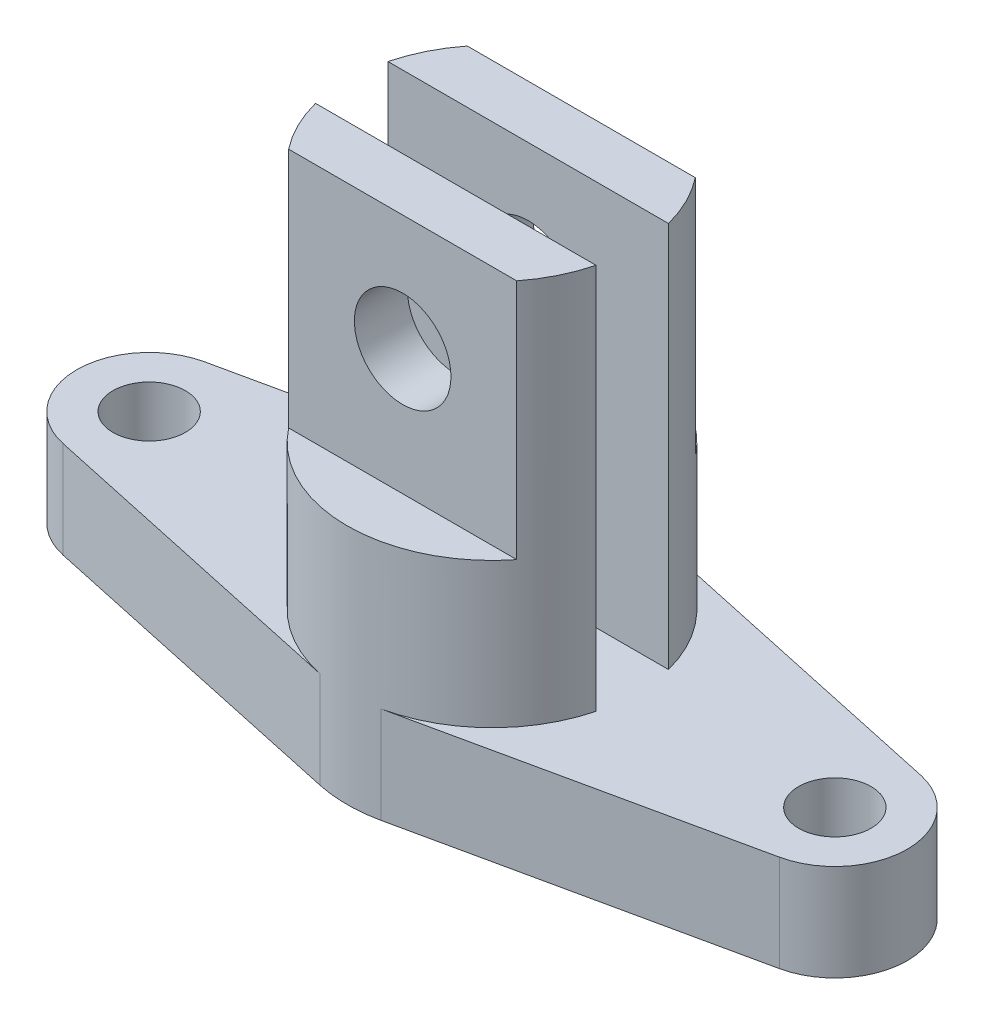
SolidWorks part; units mm, degrees
ref_plane "Alzado" through (0, 0, 0) normal (0, 0, 1) x (1, 0, 0)
ref_plane "Planta" through (0, 0, 0) normal (0, 1, 0) x (1, 0, 0)
ref_plane "Vista lateral" through (0, 0, 0) normal (1, 0, 0) x (0, 0, -1)
sketch "Croquis1" plane through (0, 0, 0) normal (0, 1, 0) x (1, 0, 0)
  line L0 (-71, 0) -> (71, 0) construction
  line L1 (-6.338, 29.3228) -> (-74.169, 14.6614)
  line L2 (-74.169, -14.6614) -> (-6.338, -29.3228)
  line L3 (74.169, 14.6614) -> (6.338, 29.3228)
  line L4 (74.169, -14.6614) -> (6.338, -29.3228)
  arc A0 (-6.338, -29.3228) -> (6.338, -29.3228) centre (0, 0) ccw
  circle A1 centre (-71, 0) radius 7.5
  circle A2 centre (71, 0) radius 7.5
  arc A3 (-74.169, 14.6614) -> (-74.169, -14.6614) centre (-71, 0) ccw
  arc A4 (74.169, 14.6614) -> (74.169, -14.6614) centre (71, 0) cw
  arc A5 (6.338, 29.3228) -> (-6.338, 29.3228) centre (0, 0) ccw
  point P5 (0, 0)
  dimension "D1" = 60
  dimension "D2" = 15
  dimension "D3" = 15
  dimension "D5" = 15
  dimension "D6" = 15
  dimension "D4" = 142
extrude "Saliente-Extruir1" add sketch "Croquis1" along normal blind 20
sketch "Croquis2" plane through (0, 20, 0) normal (0, 1, 0) x (1, 0, 0)
  line L0 (-30, 0) -> (30, 0) construction
  line L1 (-29.0474, -7.5) -> (29.0474, -7.5)
  line L2 (-29.0474, 7.5) -> (29.0474, 7.5)
  line L3 (-30, 7.5) -> (30, 7.5) construction
  line L4 (-74.169, -14.6614) -> (-6.338, -29.3228)
  line L5 (6.338, -29.3228) -> (74.169, -14.6614)
  line L6 (74.169, 14.6614) -> (6.338, 29.3228)
  line L7 (-6.338, 29.3228) -> (-74.169, 14.6614)
  line L12 (-30, -7.5) -> (30, -7.5) construction
  arc A0 (-29.0474, -7.5) -> (29.0474, -7.5) centre (0, 0) ccw
  arc A1 (29.0474, 7.5) -> (-29.0474, 7.5) centre (0, 0) ccw
  arc A4 (-74.169, 14.6614) -> (-74.169, -14.6614) centre (-71, 0) ccw
  arc A5 (-6.338, -29.3228) -> (6.338, -29.3228) centre (0, 0) ccw
  arc A6 (74.169, -14.6614) -> (74.169, 14.6614) centre (71, 0) ccw
  arc A7 (6.338, 29.3228) -> (-6.338, 29.3228) centre (0, 0) ccw
  arc A9 (-6.338, -29.3228) -> (6.338, -29.3228) centre (0, 0) ccw
  arc A11 (6.338, 29.3228) -> (-6.338, 29.3228) centre (0, 0) ccw
  arc M14 (-6.338, -29.3228) -> (6.338, -29.3228) centre (0, 0) ccw
  arc M18 (6.338, 29.3228) -> (-6.338, 29.3228) centre (0, 0) ccw
  dimension "D1" = 0
  dimension "D2" = 7.5
  dimension "D3" = 7.5
extrude "Saliente-Extruir2" add sketch "Croquis2" along normal blind 30 contours A0 L1 M14 | L2 A1 M18
sketch "Croquis3" plane through (0, 50, 0) normal (0, 1, 0) x (1, 0, 0)
  line L0 (29.0474, -7.5) -> (-29.0474, -7.5) construction
  line L1 (-29.0474, 7.5) -> (29.0474, 7.5) construction
  line L2 (29.0474, -7.5) -> (-29.0474, -7.5)
  line L3 (-29.0474, 7.5) -> (29.0474, 7.5)
  line L4 (-36.0929, 0) -> (35.9097, 0) construction
  line L5 (-23.6167, -18.5) -> (23.6167, -18.5)
  line L6 (-23.6167, 18.5) -> (23.6167, 18.5)
  line L7 (-36.0929, 18.5) -> (35.9097, 18.5) construction
  line L8 (-36.0929, -18.5) -> (35.9097, -18.5) construction
  arc A0 (-29.0474, -7.5) -> (29.0474, -7.5) centre (0, 0) ccw construction
  arc A1 (29.0474, 7.5) -> (-29.0474, 7.5) centre (0, 0) ccw construction
  arc A2 (-29.0474, -7.5) -> (-23.6167, -18.5) centre (0, 0) ccw
  arc A3 (29.0474, 7.5) -> (23.6167, 18.5) centre (0, 0) ccw
  arc A4 (-23.6167, 18.5) -> (-29.0474, 7.5) centre (0, 0) ccw
  arc A5 (23.6167, -18.5) -> (29.0474, -7.5) centre (0, 0) ccw
  point P8 (-36.0929, 0)
  point P9 (35.9097, 0)
  dimension "D1" = 18.5
  dimension "D2" = 18.5
extrude "Saliente-Extruir3" add sketch "Croquis3" along normal blind 50
sketch "Croquis4" plane through (0, 0, 18.5) normal (0, 0, 1) x (1, 0, 0)
  line L4 (-23.6167, 50) -> (23.6167, 50)
  line L5 (23.6167, 50) -> (23.6167, 100)
  line L6 (23.6167, 100) -> (-23.6167, 100)
  line L7 (-23.6167, 100) -> (-23.6167, 50)
  line L10 (23.6167, 100) -> (-23.6167, 100)
  circle A0 centre (0, 76) radius 10
  point P6 (0, 100)
  dimension "D2" = 20
  dimension "D3" = 24
  dimension "D1" = 0
extrude "Cortar-Extruir1" cut sketch "Croquis4" against normal blind 50 contours A0
